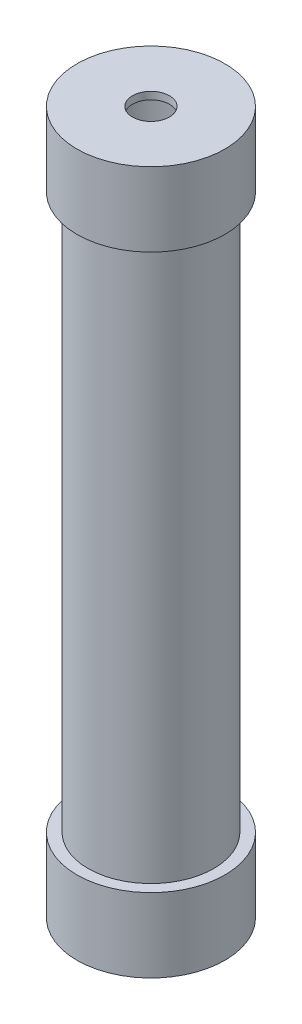
SolidWorks part; units mm, degrees
ref_plane "前视基准面" through (0, 0, 0) normal (0, 0, 1) x (1, 0, 0)
ref_plane "上视基准面" through (0, 0, 0) normal (0, 1, 0) x (1, 0, 0)
ref_plane "右视基准面" through (0, 0, 0) normal (1, 0, 0) x (0, 0, -1)
sketch "草图1" plane through (0, 0, 0) normal (0, 1, 0) x (1, 0, 0)
  line L0 (0, 20) -> (0, 15)
  line L1 (0, -15) -> (0, -20)
  arc A0 (0, -15) -> (0, 15) centre (0, 0) ccw
  arc A1 (0, -20) -> (0, 20) centre (0, 0) ccw
  dimension "D1" = 30
  dimension "D2" = 40
extrude "凸台-拉伸1" add sketch "草图1" along normal blind 20
sketch "草图2" plane through (0, 20, 0) normal (0, 1, 0) x (1, 0, 0)
  line L0 (0, 20) -> (0, 5)
  line L1 (0, -5) -> (0, -20)
  arc A0 (0, -20) -> (0, 20) centre (0, 0) ccw
  arc A1 (0, -5) -> (0, 5) centre (0, 0) ccw
  dimension "D1" = 10
extrude "凸台-拉伸2" add sketch "草图2" against normal blind 2
sketch "草图3" plane through (0, 0, 0) normal (0, 1, 0) x (1, 0, 0)
  line L0 (0, 17) -> (0, 15)
  line L1 (0, -15) -> (0, -17)
  arc A0 (0, -17) -> (0, 17) centre (0, 0) ccw
  arc A1 (0, -15) -> (0, 15) centre (0, 0) ccw
  dimension "D1" = 34
  dimension "D2" = 30
extrude "凸台-拉伸3" add sketch "草图3" against normal blind 150
sketch "草图4" plane through (0, -150, 0) normal (0, -1, 0) x (1, 0, 0)
  line L2 (0, 20) -> (0, 15)
  line L3 (0, -15) -> (0, -20)
  arc A4 (0, 20) -> (0, -20) centre (0, 0) cw
  circle A5 centre (0, 0) radius 20 construction
  arc A6 (0, 15) -> (0, -15) centre (0, 0) cw
  arc A7 (0, -15) -> (0, 15) centre (0, 0) ccw construction
extrude "凸台-拉伸4" add sketch "草图4" along normal blind 20
mirror "镜向1" of "凸台-拉伸4", "凸台-拉伸3", "凸台-拉伸2", "凸台-拉伸1"
